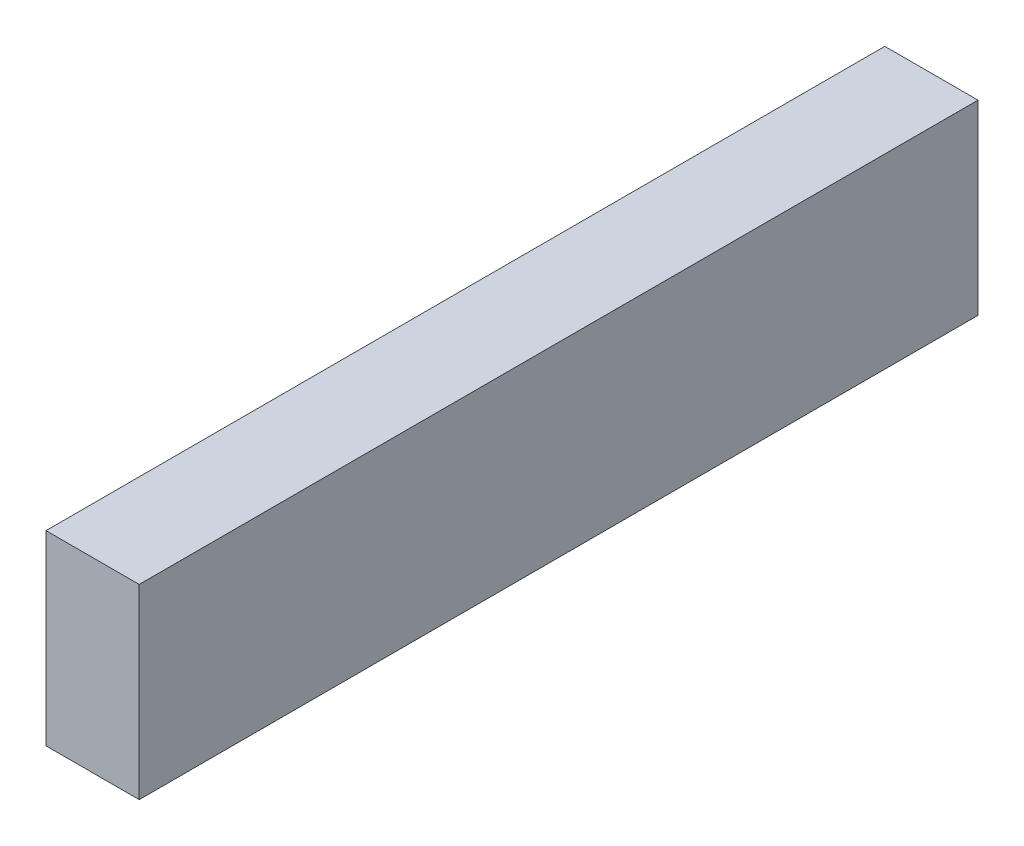
SolidWorks part; units mm, degrees
material "Plain Carbon Steel"
ref_plane "Front Plane" through (0, 0, 0) normal (0, 0, 1) x (1, 0, 0)
ref_plane "Top Plane" through (0, 0, 0) normal (0, 1, 0) x (1, 0, 0)
ref_plane "Right Plane" through (0, 0, 0) normal (1, 0, 0) x (0, 0, -1)
sketch "Sketch1" plane through (0, 0, 0) normal (0, 0, 1) x (1, 0, 0)
  line L1 (-5, -10) -> (5, -10)
  line L2 (-5, -10) -> (-5, 10)
  line L3 (-5, 10) -> (5, 10)
  line L4 (5, -10) -> (5, 10)
  line L5 (-5, -10) -> (5, 10) construction
  line L6 (-5, 10) -> (5, -10) construction
  point P0 (0, 0)
  dimension "D1" = 10
  dimension "D2" = 20
extrude "Boss-Extrude1" add sketch "Sketch1" along normal blind 90
